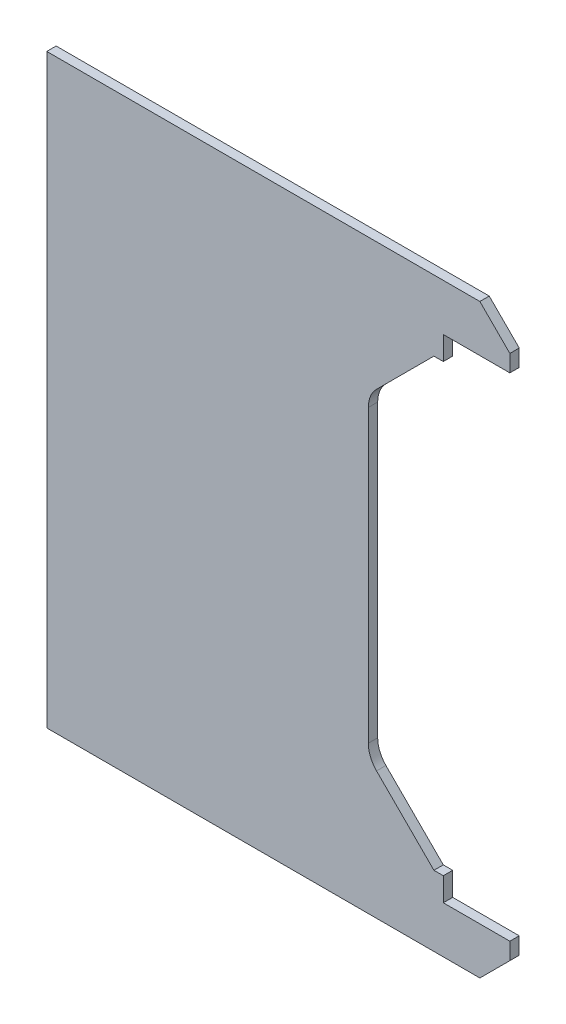
SolidWorks part; units mm, degrees
material "Liga 6061"
ref_plane "Plano frontal" through (0, 0, 0) normal (0, 0, 1) x (1, 0, 0)
ref_plane "Plano superior" through (0, 0, 0) normal (0, 1, 0) x (1, 0, 0)
ref_plane "Plano direito" through (0, 0, 0) normal (1, 0, 0) x (0, 0, -1)
sketch "Esboço1" plane through (0, 0, 0) normal (0, 0, 1) x (1, 0, 0)
  line L27 (423, 50) -> (423, 75)
  line L28 (423, 75) -> (343, 75)
  line L29 (343, 75) -> (343, 50) construction
  line L30 (462, 0) -> (494, 32)
  line L31 (494, 32) -> (494, 50)
  line L32 (494, 50) -> (343, 50) construction
  line L33 (343, 50) -> (343, 33) construction
  line L34 (335, 25) -> (0, 25) construction
  line L35 (0, 25) -> (0, 0) construction
  line L36 (0, 0) -> (462, 0)
  line L37 (423, 575) -> (343, 575) construction
  line L38 (343, 575) -> (343, 550) construction
  line L39 (343, 550) -> (423, 550)
  line L40 (423, 550) -> (423, 575)
  line L41 (343, 33) -> (343, 592) construction
  line L42 (335, 600) -> (318, 600) construction
  line L43 (318, 600) -> (318, 25) construction
  line L44 (318, 25) -> (335, 25) construction
  line L45 (494, 593) -> (462, 625)
  line L46 (462, 625) -> (0, 625)
  line L47 (0, 625) -> (0, 600) construction
  line L48 (0, 600) -> (335, 600) construction
  line L49 (343, 592) -> (343, 575) construction
  line L50 (343, 575) -> (494, 575) construction
  line L51 (494, 575) -> (494, 593)
  line L52 (0, 0) -> (0, 625)
  line L53 (423, 50) -> (494, 50)
  line L54 (423, 575) -> (494, 575)
  line L55 (343, 550) -> (343, 75)
  arc A4 (335, 25) -> (343, 33) centre (335, 33) ccw construction
  arc A5 (343, 592) -> (335, 600) centre (335, 592) ccw construction
  arc A6 (335, 25) -> (343, 33) centre (335, 33) ccw construction
  arc A7 (343, 592) -> (335, 600) centre (335, 592) ccw construction
  point P0 (343, 600)
  dimension "D4" = 8
  dimension "D1" = 625
  dimension "D2" = 25
  dimension "D3" = 343
  dimension "D5" = 50
  dimension "D6" = 25
  dimension "D8" = 45
  dimension "D9" = 45
  dimension "D10" = 18
  dimension "D11" = 423
  dimension "D12" = 462
  dimension "D13" = 25
extrude "Ressalto-extrusão1" add sketch "Esboço1" along normal blind 10
chamfer "Chanfro1" distance 70 angle 45 2 edges at (343, 75, 5) (343, 550, 5)
fillet "Filete1" radius 30 2 edges at (343, 480, 5) (343, 145, 5)
equation "\"D12@Esboço1\"=469.00mm-7"
